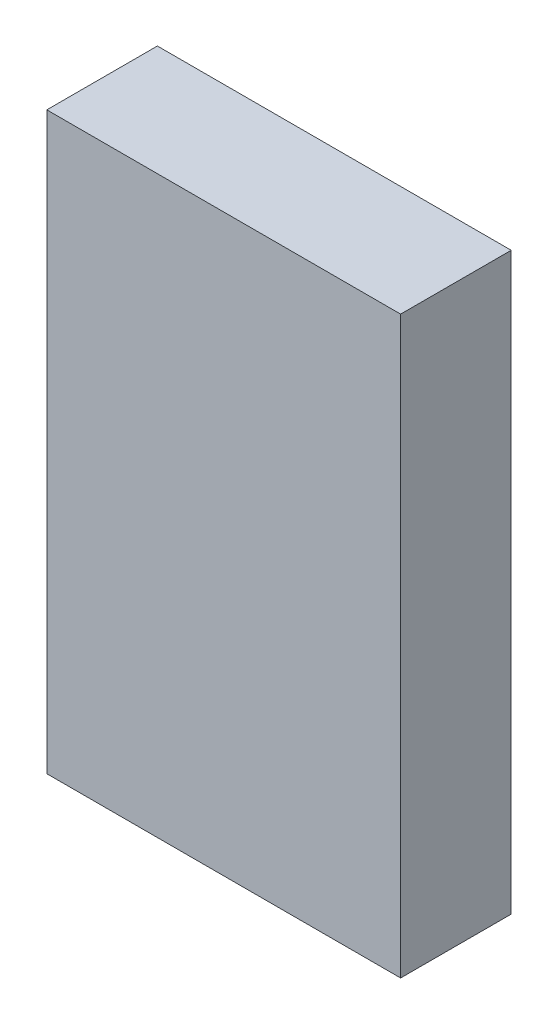
SolidWorks part; units mm, degrees
ref_plane "Front Plane" through (0, 0, 0) normal (0, 0, 1) x (1, 0, 0)
ref_plane "Top Plane" through (0, 0, 0) normal (0, 1, 0) x (1, 0, 0)
ref_plane "Right Plane" through (0, 0, 0) normal (1, 0, 0) x (0, 0, -1)
sketch "Sketch1" plane through (0, 0, 0) normal (0, 0, 1) x (1, 0, 0)
  line L0 (4380, 440) -> (4380, 570)
  line L1 (4380, 570) -> (4460, 570)
  line L2 (4460, 570) -> (4460, 440)
  line L3 (4460, 440) -> (4380, 440)
extrude "Boss-Extrude1" add sketch "Sketch1" along normal blind 25
